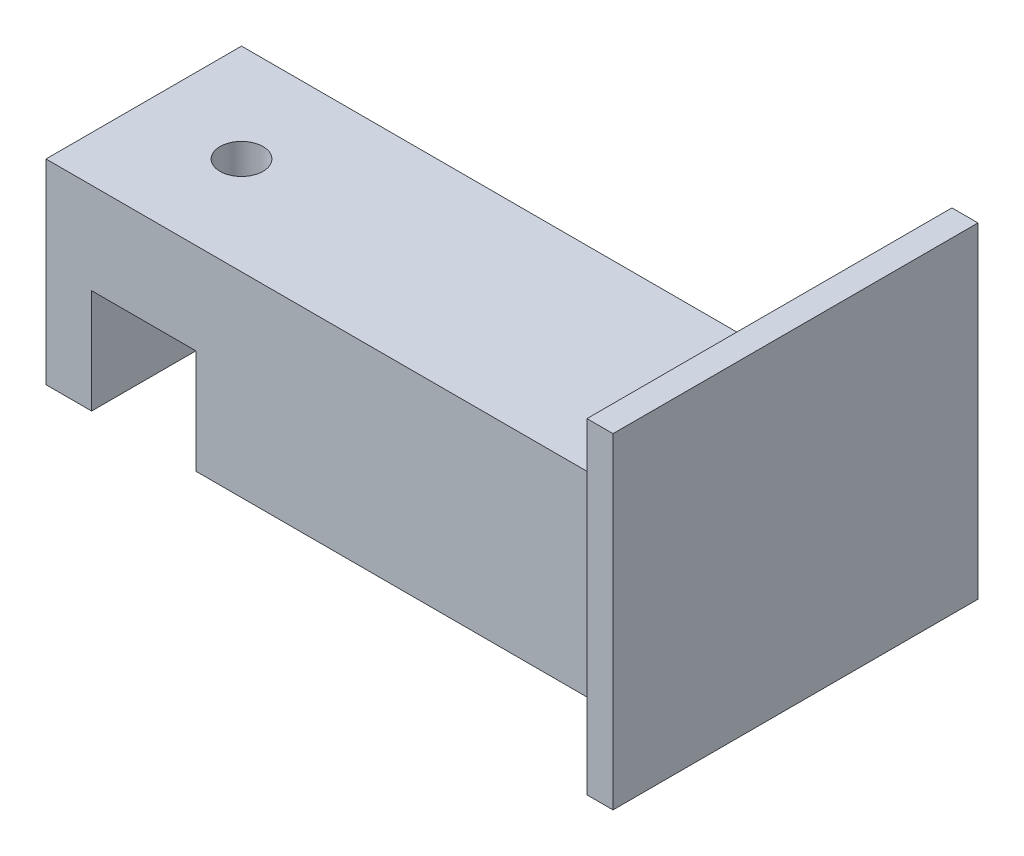
SolidWorks part; units mm, degrees
ref_plane "前视基准面" through (0, 0, 0) normal (0, 0, 1) x (1, 0, 0)
ref_plane "上视基准面" through (0, 0, 0) normal (0, 1, 0) x (1, 0, 0)
ref_plane "右视基准面" through (0, 0, 0) normal (1, 0, 0) x (0, 0, -1)
sketch "草图1" plane through (0, 0, 0) normal (0, 1, 0) x (1, 0, 0)
  line L1 (-7.5, -7.5) -> (7.5, -7.5)
  line L2 (-7.5, -7.5) -> (-7.5, 7.5)
  line L3 (-7.5, 7.5) -> (7.5, 7.5)
  line L4 (7.5, -7.5) -> (7.5, 7.5)
  line L5 (-7.5, -7.5) -> (7.5, 7.5) construction
  line L6 (-7.5, 7.5) -> (7.5, -7.5) construction
  point P0 (0, 0)
  dimension "D1" = 15
  dimension "D2" = 15
extrude "凸台-拉伸1" add sketch "草图1" against normal blind 15
sketch "草图2" plane through (0, 0, 0) normal (0, 0, 1) x (1, 0, 0)
  line L0 (-4, -7) -> (-4, -15)
  line L1 (-4, -7) -> (4, -7)
  line L2 (-4, -15) -> (4, -15)
  line L3 (4, -7) -> (4, -15)
  line L4 (-4, -7) -> (4, -15) construction
  line L5 (-4, -15) -> (4, -7) construction
  line L6 (-7.5, -15) -> (7.5, -15) construction
  point P1 (0, -11)
  dimension "D1" = 8
  dimension "D2" = 8
extrude "切除-拉伸1" cut sketch "草图2" against normal mid plane 35
sketch "草图3" plane through (0, 0, 0) normal (0, 1, 0) x (1, 0, 0)
  circle A0 centre (0, 0) radius 1.65
  dimension "D1" = 3.3
extrude "切除-拉伸2" cut sketch "草图3" against normal mid plane 35
sketch "草图5" plane through (7.5, 0, 0) normal (1, 0, 0) x (0, 0, -1)
  line L1 (-7.5, 0) -> (7.5, 0)
  line L2 (-7.5, 0) -> (-7.5, -15)
  line L3 (-7.5, -15) -> (7.5, -15)
  line L4 (7.5, 0) -> (7.5, -15)
extrude "凸台-拉伸2" add sketch "草图5" along normal blind 35
sketch "草图6" plane through (42.5, 0, 0) normal (1, 0, 0) x (0, 0, -1)
  line L0 (-14, 10) -> (-14, -15)
  line L1 (-14, 10) -> (14, 10)
  line L2 (-14, -15) -> (14, -15)
  line L3 (14, 10) -> (14, -15)
  line L4 (-14, 10) -> (14, -15) construction
  line L5 (-14, -15) -> (14, 10) construction
  line L6 (-7.5, -15) -> (7.5, -15) construction
  point P0 (-6.9263, -14.3188)
  point P1 (0, -2.5)
  dimension "D1" = 25
  dimension "D2" = 28
extrude "凸台-拉伸3" add sketch "草图6" against normal blind 2
